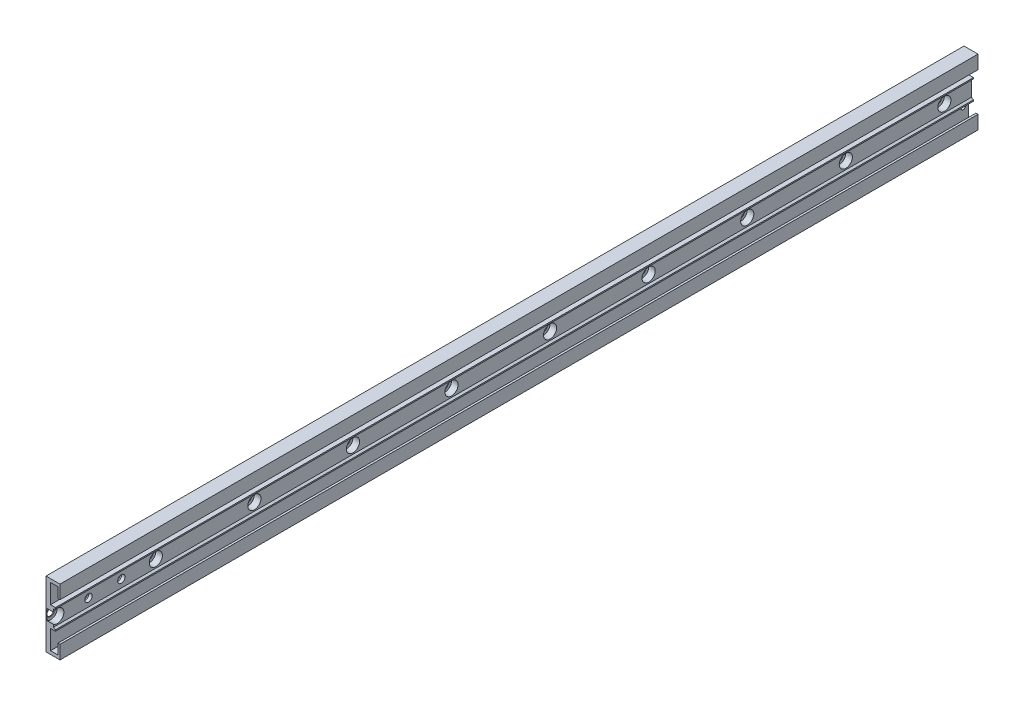
SolidWorks part; units mm, degrees
material "6061 Alloy"
ref_plane "Right Plane" through (0, 0, 0) normal (0, 0, 1) x (1, 0, 0)
ref_plane "Top Plane" through (0, 0, 0) normal (0, 1, 0) x (1, 0, 0)
ref_plane "Front Plane" through (0, 0, 0) normal (1, 0, 0) x (0, 0, -1)
sketch "Sketch1" plane through (0, 0, 0) normal (0, 0, 1) x (1, 0, 0)
  line L0 (-39.1, 20) -> (-39.1, 11.75)
  line L1 (-39.1, -20) -> (-47.625, -20)
  line L2 (-47.625, -20) -> (-47.625, 20)
  line L3 (-47.625, 20) -> (-39.1, 20)
  line L4 (-39.1, 11.75) -> (-40.375, 11.75)
  line L5 (-40.375, 11.75) -> (-40.375, 18)
  line L6 (-40.375, 18) -> (-44.875, 18)
  line L7 (-44.875, 18) -> (-44.875, 6.25)
  line L8 (-44.875, -18) -> (-40.375, -18)
  line L9 (-40.375, -18) -> (-40.375, -11.75)
  line L10 (-40.375, -11.75) -> (-39.1, -11.75)
  line L11 (-39.1, -11.75) -> (-39.1, -20)
  line L12 (-44.875, 6.25) -> (-41.875, 6.25)
  line L13 (-41.875, 6.25) -> (-41.875, 5.5)
  line L14 (-41.875, -6.25) -> (-44.875, -6.25)
  line L15 (-44.875, -6.25) -> (-44.875, -18)
  line L16 (-41.875, 5.5) -> (-43.125, 4.7783)
  line L17 (-43.125, 4.7783) -> (-43.125, -4.7783)
  line L18 (-41.875, -5.5) -> (-43.125, -4.7783)
  line L19 (-41.875, -5.5) -> (-41.875, -6.25)
  line L20 (0, 0) -> (-47.625, 0) construction
  dimension "D1" = 1.275
  dimension "D2" = 1.275
  dimension "D3" = 2
  dimension "D4" = 2
  dimension "D5" = 2.75
  dimension "D6" = 5.75
  dimension "D7" = 4.5
  dimension "D8" = 0.75
  dimension "D9" = 0.75
  dimension "D10" = 120
  dimension "D11" = 120
  dimension "D12" = 8.525
  dimension "D13" = 8.25
  dimension "D14" = 6.25
  dimension "D15" = 11.75
  dimension "D16" = 40
  dimension "D17" = 47.625
  dimension "D19" = 9.5566
extrude "Boss-Extrude1" add sketch "Sketch1" against normal blind 276.86 and the other way blind 281.94
hole_wizard "CBORE for M4 SHCS1" positions "Sketch3" profile "Sketch2" counterbore size "M4" standard "Ansi Metric" end condition through all
sketch "Sketch3" plane through (-43.125, 0, 0) normal (1, 0, 0) x (0, 0, -1)
  line L0 (-281.94, 0) -> (276.86, 0) construction
  line L1 (-281.94, -4.7783) -> (-281.94, 4.7783) construction
  line L2 (276.86, -4.7783) -> (276.86, 4.7783) construction
  point P0 (-219.59, 0)
  dimension "D1" = 62.35
sketch "Sketch2" plane through (-43.125, 0, 219.59) normal (0, 1, 0) x (0, 0, -1)
  line L0 (0, 0) -> (0, 4.5)
  line L1 (0, 4.5) -> (2.25, 4.5)
  line L3 (2.25, 4.5) -> (2.25, 4)
  line L4 (2.25, 4) -> (4, 4)
  line L5 (4, 4) -> (4, 0)
  line L7 (4, 0) -> (0, 0)
  line L11 (0, -6.35) -> (0, 107.95) construction
  dimension "Thru Hole Dia." = 4.5
  dimension "Thru Hole Depth" = 4.5
  dimension "C'Bore Dia." = 8
  dimension "C'Bore Depth" = 4
hole_wizard "CSK for M4 Flat Head Machine Screw1" positions "Sketch5" profile "Sketch4" countersink size "M4" standard "Ansi Metric" end condition through all
sketch "Sketch5" plane through (-47.625, 10.7178, -20.2582) normal (1, 0, 0) x (0, 0, -1)
  line L0 (-302.1982, -10.7178) -> (-260.8482, -10.7178) construction
  line L1 (-302.1982, -15.4961) -> (-302.1982, -5.9395) construction
  point P0 (-260.8482, -10.7178)
  point P1 (-280.8482, -10.7178)
  dimension "D1" = 21.35
  dimension "D2" = 20
sketch "Sketch4" plane through (-47.625, 0, 240.59) normal (0, 1, 0) x (0, 0, 1)
  line L0 (0, 0) -> (0, 8.525)
  line L1 (0, 8.525) -> (2.25, 8.525)
  line L2 (2.25, 8.525) -> (2.25, 2.45)
  line L3 (2.25, 2.45) -> (4.7, 0)
  line L5 (4.7, 0) -> (0, 0)
  line L6 (-2.25, 2.45) -> (-4.7, 0) construction
  line L11 (0, -6.35) -> (0, 107.95) construction
  dimension "Thru Hole Dia." = 4.5
  dimension "Thru Hole Depth" = 8.525
  dimension "Near C'Sink Dia." = 9.4
  dimension "Near C'Sink Angle" = 90
pattern_linear "LPattern1" count 9 spacing 60 along (0, 0, -1) count 2 spacing 60 along (0, 0, 1) of "CBORE for M4 SHCS1"
hole_wizard "#6-32 Tapped Hole1" positions "Sketch7" profile "Sketch6" tap size "#6-32" standard "Ansi Inch" end condition through all
sketch "Sketch7" plane through (-44.875, 0, 0) normal (1, 0, 0) x (0, 0, -1)
  line L0 (276.86, -18) -> (276.86, -6.25) construction
  line L1 (276.86, 6.25) -> (276.86, 18) construction
  line L2 (-281.94, -6.25) -> (276.86, -6.25) construction
  line L3 (-281.94, 6.25) -> (276.86, 6.25) construction
  point P0 (273.685, -9.25)
  point P1 (273.685, 9.25)
  dimension "D1" = 3.175
  dimension "D2" = 3.175
  dimension "D3" = 3
  dimension "D4" = 3
sketch "Sketch6" plane through (-44.875, -9.25, -273.685) normal (0, 1, 0) x (0, 0, -1)
  line L0 (0, 0) -> (0, 2.75)
  line L1 (0, 2.75) -> (1.3525, 2.75)
  line L2 (1.3525, 2.75) -> (1.3525, 0)
  line L5 (1.3525, 0) -> (0, 0)
  line L11 (0, -6.35) -> (0, 107.95) construction
  dimension "Thru Tap Drill Dia." = 2.7051
  dimension "Thru Tap Drill Depth" = 2.75
cosmetic thread "Hole Thread3" parameters "D2"=3.5052
cosmetic thread "Hole Thread4" parameters "D2"=3.5052
